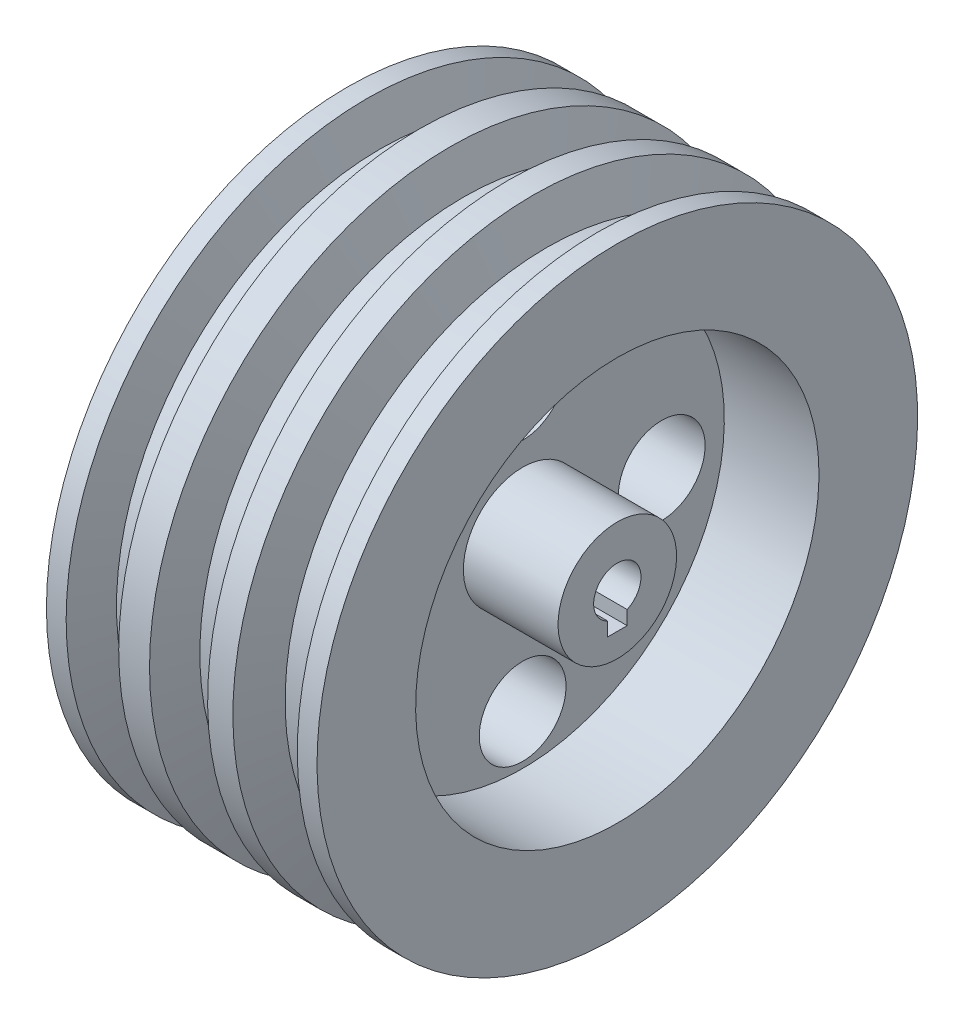
SolidWorks part; units mm, degrees
ref_plane "Front Plane" through (0, 0, 0) normal (0, 0, 1) x (1, 0, 0)
ref_plane "Top Plane" through (0, 0, 0) normal (0, 1, 0) x (1, 0, 0)
ref_plane "Right Plane" through (0, 0, 0) normal (1, 0, 0) x (0, 0, -1)
sketch "Sketch1" plane through (0, 0, 0) normal (0, 0, 1) x (1, 0, 0)
  line L1 (74.1795, 3.3077) -> (-89.4103, 3.3077) construction
  line L2 (-35, 9.3077) -> (35, 9.3077)
  line L3 (35, 9.3077) -> (35, 18.3333)
  line L4 (35, 18.3333) -> (11, 18.3333)
  line L5 (11, 18.3333) -> (11, 54.4359)
  line L6 (-11, 18.3333) -> (-35, 18.3333)
  line L7 (-35, 9.3077) -> (-35, 18.3333)
  line L8 (-11, 18.3333) -> (-11, 54.6055)
  line L9 (-11, 54.6055) -> (-33.424, 54.6055)
  line L10 (11, 54.4359) -> (35, 54.4359)
  line L11 (-35, 9.3077) -> (-35, 3.3077)
  line L12 (35, 9.3077) -> (35, 3.3077)
  line L13 (-33.424, 54.6055) -> (-33.424, 79.6055)
  line L14 (-33.424, 79.6055) -> (-28.424, 79.6055)
  line L15 (-28.424, 79.6055) -> (-25.0199, 70.253)
  line L16 (-22.5147, 79.4359) -> (-22.5147, 64.5897) construction
  line L17 (0, 64.5897) -> (0, 98.2517) construction
  line L18 (-25.0199, 70.253) -> (-18.5542, 70.253)
  line L19 (-18.5542, 70.253) -> (-15.1773, 79.5309)
  line L20 (-15.1773, 79.5309) -> (-7.3649, 79.5309)
  line L21 (-7.3649, 79.5309) -> (-3.9608, 70.1784)
  line L22 (-3.9608, 70.1784) -> (3.9105, 70.1784)
  line L23 (3.9105, 70.1784) -> (7.2874, 79.4563)
  line L24 (7.2874, 79.4563) -> (13.6942, 79.4563)
  line L25 (13.6942, 79.4563) -> (17.2266, 69.7512)
  line L26 (17.2266, 69.7512) -> (26.4751, 69.7512)
  line L27 (26.4751, 69.7512) -> (30, 79.4359)
  line L28 (30, 79.4359) -> (35, 79.4359)
  line L29 (35, 79.4359) -> (35, 54.4359)
  line L30 (21.3399, 79.4359) -> (21.3399, 64.5897) construction
  point P36 (32.5, 79.4359)
  point P37 (0, 0)
  point P38 (0, 0)
  point P39 (21.8508, 69.7512)
  point P40 (0, 0)
  point P41 (0, 81.4207)
  dimension "D5" = 25
  dimension "D7" = 5
  dimension "D8" = 5
  dimension "D9" = 20
  dimension "D10" = 20
  dimension "D11" = 20
  dimension "D12" = 20
  dimension "D13" = 20
  dimension "D14" = 70.1282
  dimension "D15" = 9.6847
  dimension "D16" = 6
revolve "Revolve3" add sketch "Sketch1" angle 360 about L1
sketch "Sketch2" plane through (11, 0, 0) normal (1, 0, 0) x (0, 0, -1)
  circle A0 centre (0, 35.2569) radius 11
  circle A1 centre (35.2569, 0) radius 11
  circle A2 centre (0, -35.2569) radius 11
  circle A3 centre (-35.2569, 0) radius 11
  dimension "D1" = 22
  dimension "D2" = 4
extrude "Cut-Extrude1" cut sketch "Sketch2" against normal through all contours A3 | A1 | A2 | A0
sketch "Sketch3" plane through (-35, 0, 0) normal (-1, 0, 0) x (0, 0, 1)
  line L1 (-2.5, 0.3077) -> (2.5, 0.3077)
  line L2 (-2.5, 0.3077) -> (-2.5, -5.6923)
  line L3 (-2.5, -5.6923) -> (2.5, -5.6923)
  line L4 (2.5, 0.3077) -> (2.5, -5.6923)
  line L5 (-2.5, 0.3077) -> (2.5, -5.6923) construction
  line L6 (-2.5, -5.6923) -> (2.5, 0.3077) construction
  circle A0 centre (0, 3.3077) radius 6 construction
  point P0 (0, -2.6923)
  dimension "D1" = 5
  dimension "D2" = 6
extrude "Cut-Extrude2" cut sketch "Sketch3" against normal through all
